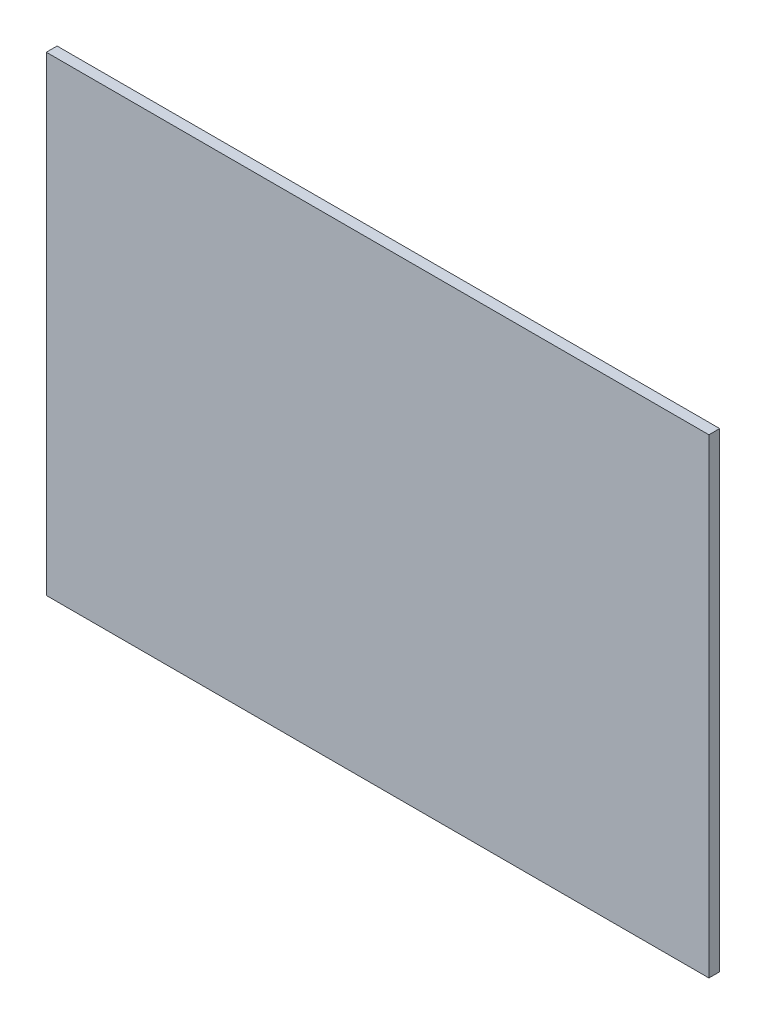
SolidWorks part; units mm, degrees
ref_plane "Front" through (0, 0, 0) normal (0, 0, 1) x (1, 0, 0)
ref_plane "Top" through (0, 0, 0) normal (0, 1, 0) x (1, 0, 0)
ref_plane "Right" through (0, 0, 0) normal (1, 0, 0) x (0, 0, -1)
sketch "Эскиз1" plane through (0, 0, 0) normal (0, 0, 1) x (1, 0, 0)
  line L1 (115.5, 310) -> (484.5, 310)
  line L2 (115.5, 310) -> (115.5, 48)
  line L3 (115.5, 48) -> (484.5, 48)
  line L4 (484.5, 310) -> (484.5, 48)
  dimension "D1" = 369
  dimension "D2" = 262
extrude "Бобышка-Вытянуть1" add sketch "Эскиз1" along normal blind 6
